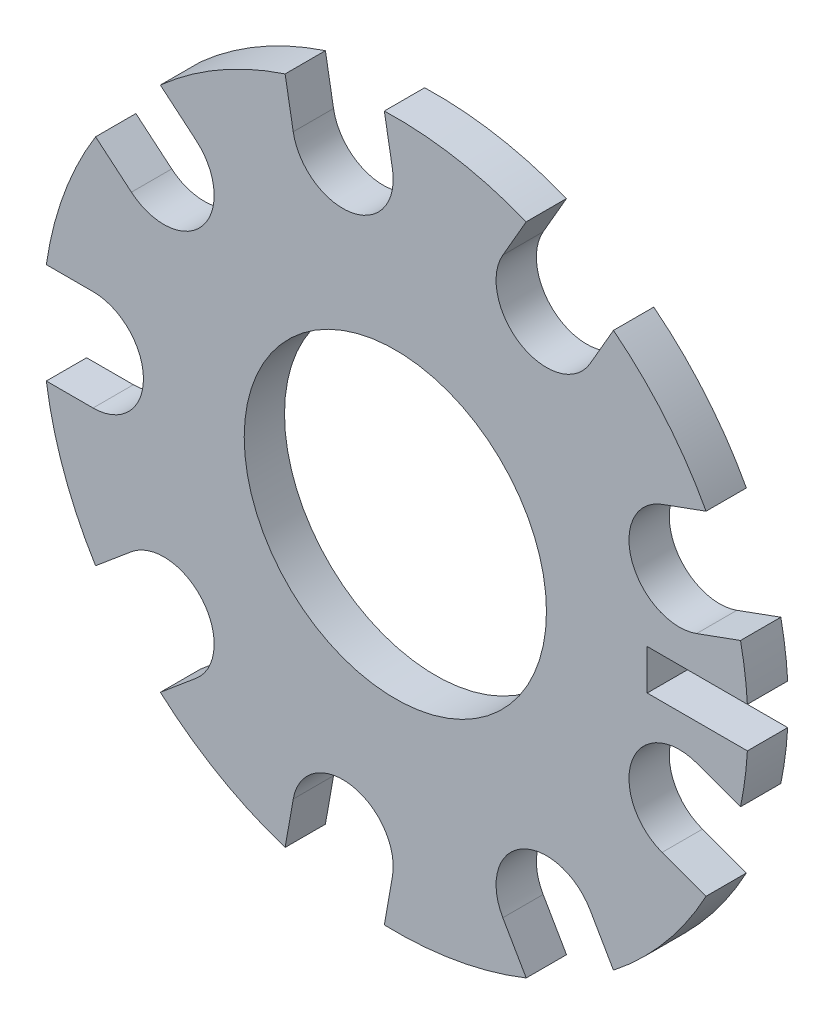
SolidWorks part; units mm, degrees
ref_plane "Front Plane" through (0, 0, 0) normal (0, 0, 1) x (1, 0, 0)
ref_plane "Top Plane" through (0, 0, 0) normal (0, 1, 0) x (1, 0, 0)
ref_plane "Right Plane" through (0, 0, 0) normal (1, 0, 0) x (0, 0, -1)
sketch "Sketch1" plane through (0, 0, 0) normal (0, 0, 1) x (1, 0, 0)
  circle A1 centre (0, 0) radius 17.5
  dimension "D2" = 35
extrude "Boss-Extrude1" add sketch "Sketch1" along normal blind 2
sketch "Sketch3" plane through (0, 0, 2) normal (0, 0, 1) x (1, 0, 0)
  line L1 (22.5, -1) -> (12.5, -1)
  line L2 (22.5, -1) -> (22.5, 1)
  line L3 (22.5, 1) -> (12.5, 1)
  line L4 (12.5, -1) -> (12.5, 1)
  line L5 (22.5, -1) -> (12.5, 1) construction
  line L6 (22.5, 1) -> (12.5, -1) construction
  circle A0 centre (0, 0) radius 17.5
  point P3 (17.5, 0)
  dimension "D3" = 35
  dimension "D1" = 2
  dimension "D2" = 10
extrude "Cut-Extrude2" cut sketch "Sketch3" against normal blind 5
sketch "Sketch4" plane through (0, 0, 2) normal (0, 0, 1) x (1, 0, 0)
  circle A0 centre (0, 0) radius 7.5
  dimension "D1" = 15
extrude "Cut-Extrude3" cut sketch "Sketch4" against normal blind 5
sketch "Sketch2" plane through (0, 0, 2) normal (0, 0, 1) x (1, 0, 0)
  line L0 (-15, 0) -> (-19.2196, 0) construction
  line L1 (-15, -2.5) -> (-19.2196, -2.5)
  line L2 (-15, 2.5) -> (-19.2196, 2.5)
  line L3 (-12.5, 3.1317) -> (-12.5, -3.8573)
  line L4 (-7.5, 3.1317) -> (-7.5, -3.8573)
  circle A5 centre (0, 0) radius 17.5
  circle A8 centre (0, 0) radius 17.5
  arc A9 (-15, -2.5) -> (-15, 2.5) centre (-15, 0) ccw
  arc A10 (-19.2196, 2.5) -> (-19.2196, -2.5) centre (-19.2196, 0) ccw
  circle A11 centre (0, 0) radius 7.5 construction
  point P5 (-17.1098, 0)
  dimension "D1" = 5
  dimension "D2" = 35
  dimension "D3" = 15
extrude "Cut-Extrude5" cut sketch "Sketch2" against normal blind 2
pattern_circular "CirPattern4" count 9 over 360 about axis through (0, 0, 0) along (0, 0, 1) of "Cut-Extrude5"
